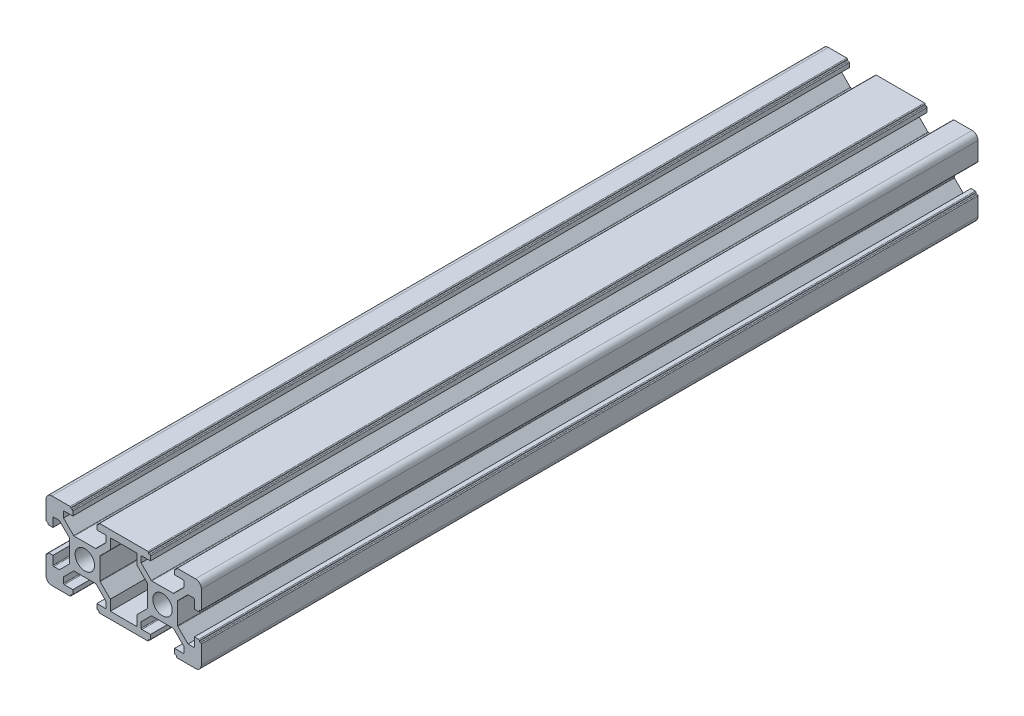
SolidWorks part; units mm, degrees
ref_plane "前视基准面" through (0, 0, 0) normal (0, 0, 1) x (1, 0, 0)
ref_plane "上视基准面" through (0, 0, 0) normal (0, 1, 0) x (1, 0, 0)
ref_plane "右视基准面" through (0, 0, 0) normal (1, 0, 0) x (0, 0, -1)
sketch "Sketch1" plane through (0, 0, 0) normal (0, 0, 1) x (1, 0, 0)
  line L0 (-8.5, 10) -> (-3.8, 10)
  line L3 (-8.5, -10) -> (-3.8, -10)
  line L5 (-10, 8.5) -> (-10, 3.8)
  line L6 (-2.7565, 3.9) -> (2.7565, 3.9)
  line L9 (-2.7565, -3.9) -> (2.7565, -3.9)
  line L10 (3.9, 2.7565) -> (3.9, -2.7565)
  line L11 (-3.9, 2.7565) -> (-3.9, -2.7565)
  line L12 (-3.9586, -2.8979) -> (-6.5607, -5.5)
  line L13 (3.6, 9.7) -> (3.6, 9.8)
  line L14 (3.1, -8.2) -> (5.3, -8.2)
  line L15 (-2.8979, -3.9586) -> (-5.5, -6.5607)
  line L16 (-3.1, -8.2) -> (-3.1, -9.3)
  line L17 (3.1, -8.2) -> (3.1, -9.3)
  line L18 (-5.5, -6.5607) -> (-5.5, -8)
  line L19 (5.5, -6.5607) -> (5.5, -8)
  line L20 (-5.3, -8.2) -> (-3.1, -8.2)
  line L21 (-3.4, -9.5) -> (-3.3, -9.5)
  line L22 (3.8, -10) -> (8.5, -10)
  line L23 (3.3, -9.5) -> (3.4, -9.5)
  line L24 (-3.6, -9.7) -> (-3.6, -9.8)
  line L25 (3.6, -9.7) -> (3.6, -9.8)
  line L26 (-6.5607, -5.5) -> (-8, -5.5)
  line L27 (-9.7, -3.6) -> (-9.8, -3.6)
  line L28 (-9.5, -3.4) -> (-9.5, -3.3)
  line L29 (-8.2, -3.1) -> (-9.3, -3.1)
  line L30 (-8.2, -5.3) -> (-8.2, -3.1)
  line L31 (-10, -3.8) -> (-10, -8.5)
  line L33 (3.8, 10) -> (8.5, 10)
  line L34 (2.8979, -3.9586) -> (5.5, -6.5607)
  line L40 (3.9586, -2.8979) -> (6.5607, -5.5)
  line L41 (3.3, 9.5) -> (3.4, 9.5)
  line L42 (30, 8.5) -> (30, 3.8)
  line L43 (3.1, 8.2) -> (3.1, 9.3)
  line L44 (3.1, 8.2) -> (5.3, 8.2)
  line L45 (5.5, 6.5607) -> (5.5, 8)
  line L46 (2.8979, 3.9586) -> (5.5, 6.5607)
  line L52 (3.9586, 2.8979) -> (6.5607, 5.5)
  line L53 (-3.6, 9.7) -> (-3.6, 9.8)
  line L54 (-3.4, 9.5) -> (-3.3, 9.5)
  line L55 (-3.1, 8.2) -> (-3.1, 9.3)
  line L56 (-5.3, 8.2) -> (-3.1, 8.2)
  line L57 (-5.5, 6.5607) -> (-5.5, 8)
  line L58 (-2.8979, 3.9586) -> (-5.5, 6.5607)
  line L59 (-9.5, 3.4) -> (-9.5, 3.3)
  line L60 (-9.7, 3.6) -> (-9.8, 3.6)
  line L61 (-8.2, 3.1) -> (-9.3, 3.1)
  line L62 (-8.2, 5.3) -> (-8.2, 3.1)
  line L63 (-6.5607, 5.5) -> (-8, 5.5)
  line L64 (-3.9586, 2.8979) -> (-6.5607, 5.5)
  line L65 (29.7, 3.6) -> (29.8, 3.6)
  line L66 (29.5, 3.4) -> (29.5, 3.3)
  line L67 (28.2, 3.1) -> (29.3, 3.1)
  line L68 (28.2, 5.3) -> (28.2, 3.1)
  line L69 (26.5607, 5.5) -> (28, 5.5)
  line L70 (23.9586, 2.8979) -> (26.5607, 5.5)
  line L71 (23.9, 2.7565) -> (23.9, -2.7565)
  line L72 (23.9586, -2.8979) -> (26.5607, -5.5)
  line L73 (26.5607, -5.5) -> (28, -5.5)
  line L74 (28.2, -5.3) -> (28.2, -3.1)
  line L75 (28.2, -3.1) -> (29.3, -3.1)
  line L76 (29.5, -3.4) -> (29.5, -3.3)
  line L77 (29.7, -3.6) -> (29.8, -3.6)
  line L78 (30, -3.8) -> (30, -8.5)
  line L79 (28.5, -10) -> (23.8, -10)
  line L80 (23.6, -9.7) -> (23.6, -9.8)
  line L81 (23.4, -9.5) -> (23.3, -9.5)
  line L82 (23.1, -8.2) -> (23.1, -9.3)
  line L83 (25.3, -8.2) -> (23.1, -8.2)
  line L84 (25.5, -6.5607) -> (25.5, -8)
  line L85 (22.8979, -3.9586) -> (25.5, -6.5607)
  line L86 (22.7565, -3.9) -> (17.2435, -3.9)
  line L87 (17.1021, -3.9586) -> (14.5, -6.5607)
  line L88 (14.5, -6.5607) -> (14.5, -8)
  line L89 (16.9, -8.2) -> (14.7, -8.2)
  line L90 (16.9, -8.2) -> (16.9, -9.3)
  line L91 (16.7, -9.5) -> (16.6, -9.5)
  line L92 (16.4, -9.7) -> (16.4, -9.8)
  line L93 (16.2, -10) -> (11.5, -10)
  line L94 (13.4393, 5.5) -> (13.4393, 8.2)
  line L96 (6.5607, 5.5) -> (6.5607, 8.2)
  line L97 (6.5607, 8.2) -> (13.4393, 8.2)
  line L99 (16.0414, -2.8979) -> (13.4393, -5.5)
  line L100 (16.1, 2.7565) -> (16.1, -2.7565)
  line L101 (16.0414, 2.8979) -> (13.4393, 5.5)
  line L107 (16.2, 10) -> (11.5, 10)
  line L108 (16.4, 9.7) -> (16.4, 9.8)
  line L109 (16.7, 9.5) -> (16.6, 9.5)
  line L110 (16.9, 8.2) -> (16.9, 9.3)
  line L111 (16.9, 8.2) -> (14.7, 8.2)
  line L112 (14.5, 6.5607) -> (14.5, 8)
  line L113 (17.1021, 3.9586) -> (14.5, 6.5607)
  line L114 (22.7565, 3.9) -> (17.2435, 3.9)
  line L115 (22.8979, 3.9586) -> (25.5, 6.5607)
  line L116 (25.5, 6.5607) -> (25.5, 8)
  line L117 (25.3, 8.2) -> (23.1, 8.2)
  line L118 (23.1, 8.2) -> (23.1, 9.3)
  line L119 (23.4, 9.5) -> (23.3, 9.5)
  line L120 (23.6, 9.7) -> (23.6, 9.8)
  line L121 (28.5, 10) -> (23.8, 10)
  line L122 (13.4393, -5.5) -> (13.4393, -8.2)
  line L124 (6.5607, -5.5) -> (6.5607, -8.2)
  line L125 (6.5607, -8.2) -> (13.4393, -8.2)
  line L127 (8.5, 10) -> (11.5, 10)
  line L128 (8.5, -10) -> (11.5, -10)
  arc A3 (-8.5, -10) -> (-10, -8.5) centre (-8.5, -8.5) cw
  arc A4 (-10, 8.5) -> (-8.5, 10) centre (-8.5, 8.5) cw
  arc A5 (3.4, -9.5) -> (3.6, -9.7) centre (3.4, -9.7) cw
  arc A6 (3.8, -10) -> (3.6, -9.8) centre (3.8, -9.8) cw
  arc A7 (3.3, -9.5) -> (3.1, -9.3) centre (3.3, -9.3) cw
  arc A8 (5.3, -8.2) -> (5.5, -8) centre (5.3, -8) ccw
  arc A9 (-3.9, -2.7565) -> (-3.9586, -2.8979) centre (-4.1, -2.7565) cw
  arc A10 (-3.9, 2.7565) -> (-3.9586, 2.8979) centre (-4.1, 2.7565) ccw
  arc A11 (-2.7565, 3.9) -> (-2.8979, 3.9586) centre (-2.7565, 4.1) cw
  arc A12 (2.7565, 3.9) -> (2.8979, 3.9586) centre (2.7565, 4.1) ccw
  arc A13 (3.9586, 2.8979) -> (3.9, 2.7565) centre (4.1, 2.7565) ccw
  arc A14 (3.9, -2.7565) -> (3.9586, -2.8979) centre (4.1, -2.7565) ccw
  arc A15 (-2.8979, -3.9586) -> (-2.7565, -3.9) centre (-2.7565, -4.1) cw
  arc A16 (2.7565, -3.9) -> (2.8979, -3.9586) centre (2.7565, -4.1) cw
  arc A17 (-3.6, -9.8) -> (-3.8, -10) centre (-3.8, -9.8) cw
  arc A18 (-3.3, -9.5) -> (-3.1, -9.3) centre (-3.3, -9.3) ccw
  arc A19 (-3.6, -9.7) -> (-3.4, -9.5) centre (-3.4, -9.7) cw
  arc A20 (-8.2, 5.3) -> (-8, 5.5) centre (-8, 5.3) cw
  arc A23 (-8.2, -5.3) -> (-8, -5.5) centre (-8, -5.3) ccw
  arc A24 (-5.3, -8.2) -> (-5.5, -8) centre (-5.3, -8) cw
  arc A31 (3.1, 9.3) -> (3.3, 9.5) centre (3.3, 9.3) cw
  arc A32 (3.6, 9.8) -> (3.8, 10) centre (3.8, 9.8) cw
  arc A33 (3.6, 9.7) -> (3.4, 9.5) centre (3.4, 9.7) cw
  arc A34 (-3.8, 10) -> (-3.6, 9.8) centre (-3.8, 9.8) cw
  arc A35 (-3.3, 9.5) -> (-3.1, 9.3) centre (-3.3, 9.3) cw
  arc A36 (-3.4, 9.5) -> (-3.6, 9.7) centre (-3.4, 9.7) cw
  arc A37 (5.5, 8) -> (5.3, 8.2) centre (5.3, 8) ccw
  arc A38 (-5.5, 8) -> (-5.3, 8.2) centre (-5.3, 8) cw
  arc A39 (-10, 3.8) -> (-9.8, 3.6) centre (-9.8, 3.8) ccw
  arc A40 (-9.5, 3.3) -> (-9.3, 3.1) centre (-9.3, 3.3) ccw
  arc A41 (-9.7, 3.6) -> (-9.5, 3.4) centre (-9.7, 3.4) cw
  arc A42 (-10, -3.8) -> (-9.8, -3.6) centre (-9.8, -3.8) cw
  arc A43 (-9.5, -3.3) -> (-9.3, -3.1) centre (-9.3, -3.3) cw
  arc A44 (-9.5, -3.4) -> (-9.7, -3.6) centre (-9.7, -3.4) cw
  arc A45 (30, 8.5) -> (28.5, 10) centre (28.5, 8.5) ccw
  arc A46 (30, 3.8) -> (29.8, 3.6) centre (29.8, 3.8) cw
  arc A47 (29.7, 3.6) -> (29.5, 3.4) centre (29.7, 3.4) ccw
  arc A48 (29.5, 3.3) -> (29.3, 3.1) centre (29.3, 3.3) cw
  arc A49 (28.2, 5.3) -> (28, 5.5) centre (28, 5.3) ccw
  arc A50 (23.9, 2.7565) -> (23.9586, 2.8979) centre (24.1, 2.7565) cw
  arc A51 (23.9, -2.7565) -> (23.9586, -2.8979) centre (24.1, -2.7565) ccw
  arc A52 (28.2, -5.3) -> (28, -5.5) centre (28, -5.3) cw
  arc A53 (29.5, -3.3) -> (29.3, -3.1) centre (29.3, -3.3) ccw
  arc A54 (29.5, -3.4) -> (29.7, -3.6) centre (29.7, -3.4) ccw
  arc A55 (30, -3.8) -> (29.8, -3.6) centre (29.8, -3.8) ccw
  arc A56 (28.5, -10) -> (30, -8.5) centre (28.5, -8.5) ccw
  arc A57 (23.6, -9.8) -> (23.8, -10) centre (23.8, -9.8) ccw
  arc A58 (23.6, -9.7) -> (23.4, -9.5) centre (23.4, -9.7) ccw
  arc A59 (23.3, -9.5) -> (23.1, -9.3) centre (23.3, -9.3) cw
  arc A60 (25.3, -8.2) -> (25.5, -8) centre (25.3, -8) ccw
  arc A61 (22.8979, -3.9586) -> (22.7565, -3.9) centre (22.7565, -4.1) ccw
  arc A62 (17.2435, -3.9) -> (17.1021, -3.9586) centre (17.2435, -4.1) ccw
  arc A63 (14.7, -8.2) -> (14.5, -8) centre (14.7, -8) cw
  arc A64 (16.7, -9.5) -> (16.9, -9.3) centre (16.7, -9.3) ccw
  arc A65 (16.6, -9.5) -> (16.4, -9.7) centre (16.6, -9.7) ccw
  arc A66 (16.2, -10) -> (16.4, -9.8) centre (16.2, -9.8) ccw
  arc A72 (16.1, -2.7565) -> (16.0414, -2.8979) centre (15.9, -2.7565) cw
  arc A73 (16.0414, 2.8979) -> (16.1, 2.7565) centre (15.9, 2.7565) cw
  arc A79 (16.4, 9.8) -> (16.2, 10) centre (16.2, 9.8) ccw
  arc A80 (16.4, 9.7) -> (16.6, 9.5) centre (16.6, 9.7) ccw
  arc A81 (16.9, 9.3) -> (16.7, 9.5) centre (16.7, 9.3) ccw
  arc A82 (14.5, 8) -> (14.7, 8.2) centre (14.7, 8) cw
  arc A83 (17.2435, 3.9) -> (17.1021, 3.9586) centre (17.2435, 4.1) cw
  arc A84 (22.7565, 3.9) -> (22.8979, 3.9586) centre (22.7565, 4.1) ccw
  arc A85 (25.5, 8) -> (25.3, 8.2) centre (25.3, 8) ccw
  arc A86 (23.3, 9.5) -> (23.1, 9.3) centre (23.3, 9.3) ccw
  arc A87 (23.4, 9.5) -> (23.6, 9.7) centre (23.4, 9.7) ccw
  arc A88 (23.8, 10) -> (23.6, 9.8) centre (23.8, 9.8) ccw
  point P11 (3.9, 3.9)
  point P19 (3.3697, 4.4303)
  point P20 (-10.6428, -10.6428)
  point P25 (-11.1731, -10.1124)
  point P26 (4.4303, 3.3697)
  point P28 (-10.1124, -11.1731)
  dimension "D3" = 0.2
  dimension "D4" = 0.2
  dimension "D5" = 0.2
  dimension "D8" = 0.2
  dimension "D9" = 0.2
  dimension "D10" = 0.2
  dimension "D6" = 1.8
  dimension "D7" = 0.5
extrude "Boss-Extrude1" add sketch "Sketch1" along normal blind 200
ref_plane "hole" through (0, 0, 200) normal (0, 0, 1) x (1, 0, 0)
sketch "Sketch2" plane through (0, 0, 200) normal (0, 0, 1) x (1, 0, 0)
  circle A0 centre (0, 0) radius 2.5
  circle A1 centre (20, 0) radius 2.5
  dimension "D1" = 5
extrude "Cut-Extrude1" cut sketch "Sketch2" against normal through all
sketch "Sketch3" plane through (23.9, 0, 0) normal (1, 0, 0) x (0, 0, -1)
  line L0 (-200, -2.7565) -> (-200, 2.7565) construction
  circle A0 centre (-183.3, 0) radius 1.5
  circle A1 centre (-166.6, 0) radius 1.5
  point P6 (-200, 0)
  dimension "D1" = 16.7
  dimension "D2" = 16.7
  dimension "D3" = 0
  dimension "D4" = 0
  dimension "D5" = 3
  dimension "D6" = 3
extrude "Cut-Extrude2" cut sketch "Sketch3" against normal blind 49
